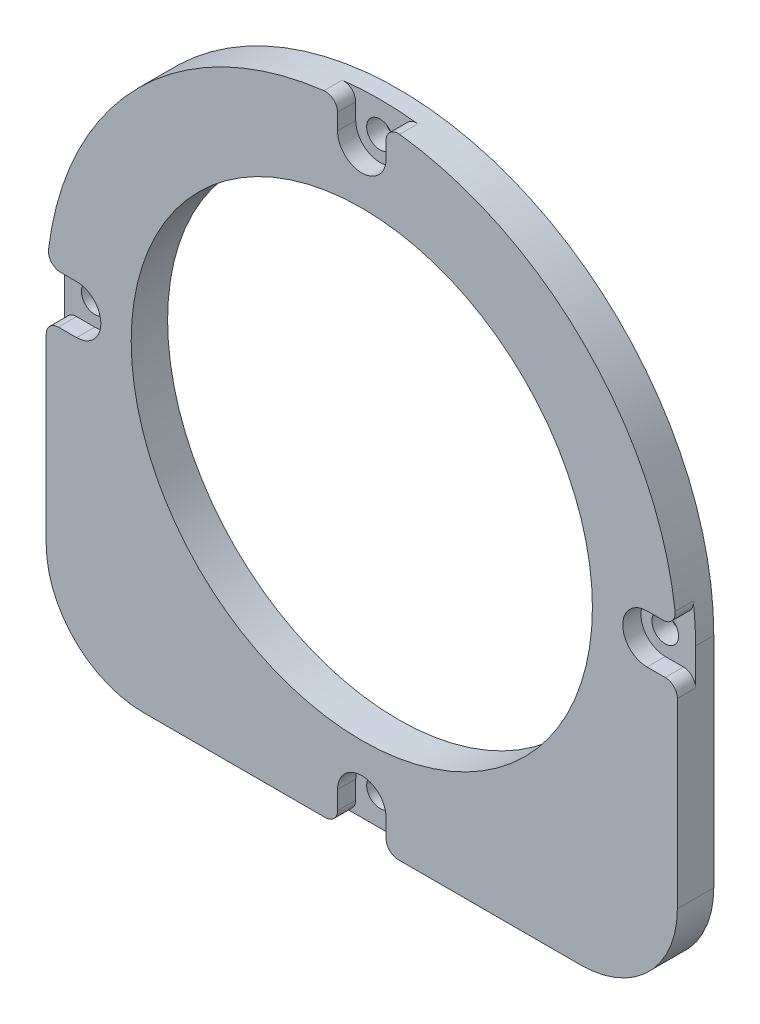
SolidWorks part; units mm, degrees
ref_plane "Спереди" through (0, 0, 0) normal (0, 0, 1) x (1, 0, 0)
ref_plane "Сверху" through (0, 0, 0) normal (0, 1, 0) x (1, 0, 0)
ref_plane "Справа" through (0, 0, 0) normal (1, 0, 0) x (0, 0, -1)
sketch "Эскиз1" plane through (0, 0, 0) normal (0, 0, 1) x (1, 0, 0)
  line L0 (-26, 0) -> (-26, -26)
  line L1 (-26, -26) -> (26, -26)
  line L2 (26, -26) -> (26, 0)
  circle A0 centre (0, 0) radius 19
  arc A1 (26, 0) -> (-26, 0) centre (0, 0) ccw
  arc A2 (-26, 0) -> (0, -26) centre (0, 0) ccw construction
  arc A3 (0, -26) -> (26, 0) centre (0, 0) ccw construction
  dimension "D1" = 38
  dimension "D2" = 52
extrude "Бобышка-Вытянуть1" add sketch "Эскиз1" along normal blind 3
sketch "Эскиз2" plane through (0, 0, 3) normal (0, 0, 1) x (1, 0, 0)
  circle A0 centre (0, 0) radius 23.5 construction
  circle A1 centre (0, 23.5) radius 1.1
  circle A2 centre (23.5, 0) radius 1.1
  circle A3 centre (0, -23.5) radius 1.1
  circle A4 centre (-23.5, 0) radius 1.1
  dimension "D1" = 47
  dimension "D2" = 2.2
  dimension "D3" = 4
extrude "Вырез-Вытянуть1" cut sketch "Эскиз2" against normal through all
sketch "Эскиз3" plane through (0, 0, 3) normal (0, 0, 1) x (1, 0, 0)
  line L0 (-2, 23.5) -> (-2, 26)
  line L1 (-2, 26) -> (2, 26)
  line L2 (2, 26) -> (2, 23.5)
  line L3 (26, -2) -> (23.5, -2)
  line L4 (26, 2) -> (26, -2)
  line L5 (23.5, 2) -> (26, 2)
  line L6 (-2, -26) -> (-2, -23.5)
  line L7 (2, -26) -> (-2, -26)
  line L8 (2, -23.5) -> (2, -26)
  line L9 (-26, 2) -> (-23.5, 2)
  line L10 (-26, -2) -> (-26, 2)
  line L11 (-23.5, -2) -> (-26, -2)
  arc A0 (-2, 23.5) -> (2, 23.5) centre (0, 23.5) ccw
  arc A1 (26, 0) -> (-26, 0) centre (0, 0) ccw construction
  arc A2 (2, 23.5) -> (-2, 23.5) centre (0, 23.5) ccw construction
  arc A3 (23.5, 2) -> (23.5, -2) centre (23.5, 0) ccw
  arc A4 (2, -23.5) -> (-2, -23.5) centre (0, -23.5) ccw
  arc A5 (-23.5, -2) -> (-23.5, 2) centre (-23.5, 0) ccw
  circle A6 centre (23.5, 0) radius 1.1 construction
  dimension "D1" = 4
  dimension "D2" = 4
extrude "Вырез-Вытянуть2" cut sketch "Эскиз3" against normal blind 1.5
fillet "Скругление1" radius 1 8 edges at (25.923, 2, 2.25) (26, -2, 2.25) (-2, 25.923, 2.25) (2, 25.923, 2.25) (-26, -2, 2.25) (-25.923, 2, 2.25) (2, -26, 2.25) (-2, -26, 2.25)
fillet "Скругление2" radius 8 2 edges at (-26, -26, 1.5) (26, -26, 1.5)
equation "\"big_bearing_d1\"= 19.9"
equation "\"big_bearing_d2\"= 42"
equation "\"big_bearing_h\"= 11.9"
equation "\"print_offset\"= 0.5"
equation "\"small_bearing_d1\"= 2.9"
equation "\"small_bearing_d2\"= 10"
equation "\"small_bearing_h\"= 4"
equation "\"tube_d\"= 16"
equation "\"small_bearing_distance\"= 2"
equation "\"D1@Эскиз1\"=\"big_bearing_d2\"-4"
equation "\"D2@Эскиз1\"=\"big_bearing_d2\"+10"
